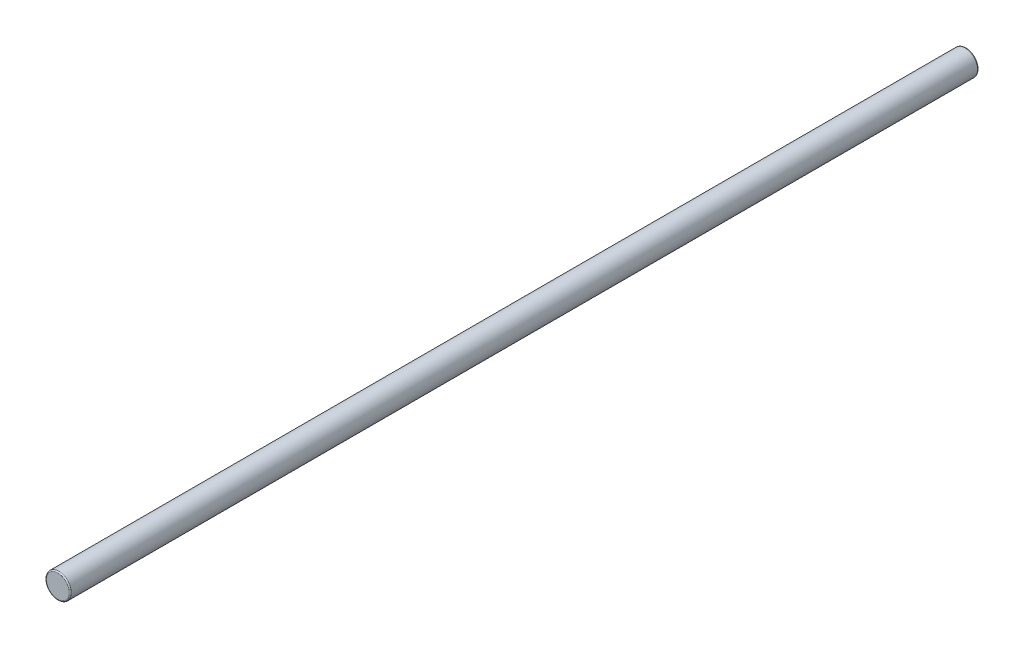
SolidWorks part; units mm, degrees
ref_plane "Plano frontal" through (0, 0, 0) normal (0, 0, 1) x (1, 0, 0)
ref_plane "Plano superior" through (0, 0, 0) normal (0, 1, 0) x (1, 0, 0)
ref_plane "Plano direito" through (0, 0, 0) normal (1, 0, 0) x (0, 0, -1)
sketch "Esboço1" plane through (0, 0, 0) normal (0, 0, 1) x (1, 0, 0)
  circle A0 centre (0, 0) radius 0.55
  dimension "D1" = 1.1
extrude "Ressalto-extrusão1" add sketch "Esboço1" along normal blind 40
fillet "Filete1" radius 0.05 2 edges at (0.55, 0, 0) (0.55, 0, 40)
